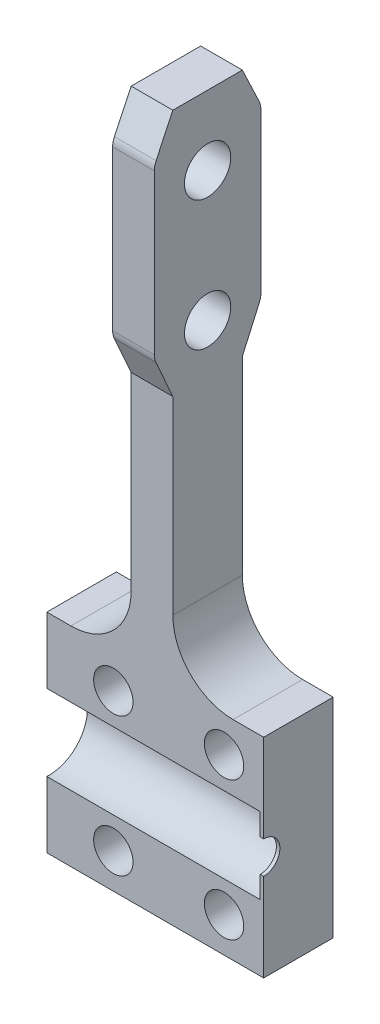
SolidWorks part; units mm, degrees
ref_plane "Front Plane" through (0, 0, 0) normal (0, 0, 1) x (1, 0, 0)
ref_plane "Top Plane" through (0, 0, 0) normal (0, 1, 0) x (1, 0, 0)
ref_plane "Right Plane" through (0, 0, 0) normal (1, 0, 0) x (0, 0, -1)
sketch "Sketch1" plane through (0, 0, 0) normal (0, 0, 1) x (1, 0, 0)
  line L0 (-26.3, 129.9) -> (39.7021, 129.9) construction
  line L1 (-8.1, 22.5) -> (-8.1, 129.9)
  line L3 (0.9, 35.5) -> (0.9, 129.9)
  line L5 (-8.1, 129.9) -> (0.9, 129.9)
  line L12 (-26.3, 22.5) -> (-26.3, -22.5)
  line L13 (-26.3, -22.5) -> (20.5, -22.5)
  line L14 (20.5, -22.5) -> (20.5, 22.5)
  line L15 (20.5, 22.5) -> (13.9, 22.5)
  line L17 (-8.1, 22.5) -> (-26.3, 22.5)
  circle A4 centre (-11.95, -14.95) radius 4.25
  circle A5 centre (11.95, -14.95) radius 4.25
  circle A6 centre (11.95, 14.95) radius 4.25
  circle A7 centre (-11.95, 14.95) radius 4.25
  arc A8 (0.9, 35.5) -> (13.9, 22.5) centre (13.9, 35.5) ccw
  point P32 (-8.1, 22.5)
  dimension "D4" = 13
  dimension "D3" = 9
extrude "Boss-Extrude1" add sketch "Sketch1" along normal blind 15
sketch "Sketch3" plane through (-26.3, 0, 0) normal (-1, 0, 0) x (0, 0, 1)
  line L0 (15, 0) -> (-12.6668, 0) construction
  line L1 (15, 22.5) -> (15, -22.5) construction
  circle A0 centre (14.5, 0) radius 8.25
  point P7 (0, 0)
  dimension "D2" = 16.5
  dimension "D1" = 0.5
extrude "Cut-Extrude1" cut sketch "Sketch3" against normal blind 46.05
sketch "Sketch4" plane through (0.9, 0, 0) normal (1, 0, 0) x (0, 0, -1)
  line L0 (-7.5, 22.5) -> (-7.5, 86.9) construction
  line L1 (-15, 22.5) -> (0, 22.5) construction
  circle A0 centre (-7.5, 86.9) radius 5
  circle A1 centre (-7.5, 114.9) radius 5
  point P7 (0, 0)
  point P8 (0, 0)
  point P9 (0, 0)
  dimension "D1" = 10
  dimension "D2" = 28
extrude "Cut-Extrude3" cut sketch "Sketch4" against normal blind 46.05
sketch "Sketch5" plane through (20.5, 0, 0) normal (1, 0, 0) x (0, 0, -1)
  line L0 (-15, -22.5) -> (-15, 22.5) construction
  circle A0 centre (-15, 0) radius 3.5
extrude "Cut-Extrude4" cut sketch "Sketch5" against normal blind 46.05
sketch "Sketch6" plane through (-8.1, 0, 0) normal (-1, 0, 0) x (0, 0, 1)
  line L0 (15, 76.3869) -> (18.6516, 84.5541)
  line L1 (15, 129.9) -> (15, 22.5) construction
  line L2 (19, 86.1868) -> (19, 120.55)
  line L3 (18.6155, 122.2613) -> (15, 129.9)
  line L4 (7.5, 114.9) -> (7.5, 65.4139) construction
  line L5 (-3.6155, 122.2613) -> (0, 129.9)
  line L6 (-4, 86.1868) -> (-4, 120.55)
  line L7 (0, 76.3869) -> (-3.6516, 84.5541)
  line L8 (0, 76.3869) -> (0, 129.9)
  line L9 (15, 76.3869) -> (15, 129.9)
  arc A0 (19, 120.55) -> (18.6155, 122.2613) centre (15, 120.55) ccw
  arc A1 (18.6516, 84.5541) -> (19, 86.1868) centre (15, 86.1868) ccw
  arc A2 (-3.6516, 84.5541) -> (-4, 86.1868) centre (0, 86.1868) cw
  arc A3 (-4, 120.55) -> (-3.6155, 122.2613) centre (0, 120.55) cw
  dimension "D1" = 4
  dimension "D2" = 4
extrude "Boss-Extrude2" add sketch "Sketch6" against normal up to surface (9 mm away) up to face at (0.9, 86.9, 2.5)
fillet "Fillet1" radius 13 1 edges at (-8.1, 22.5, 7.5)
